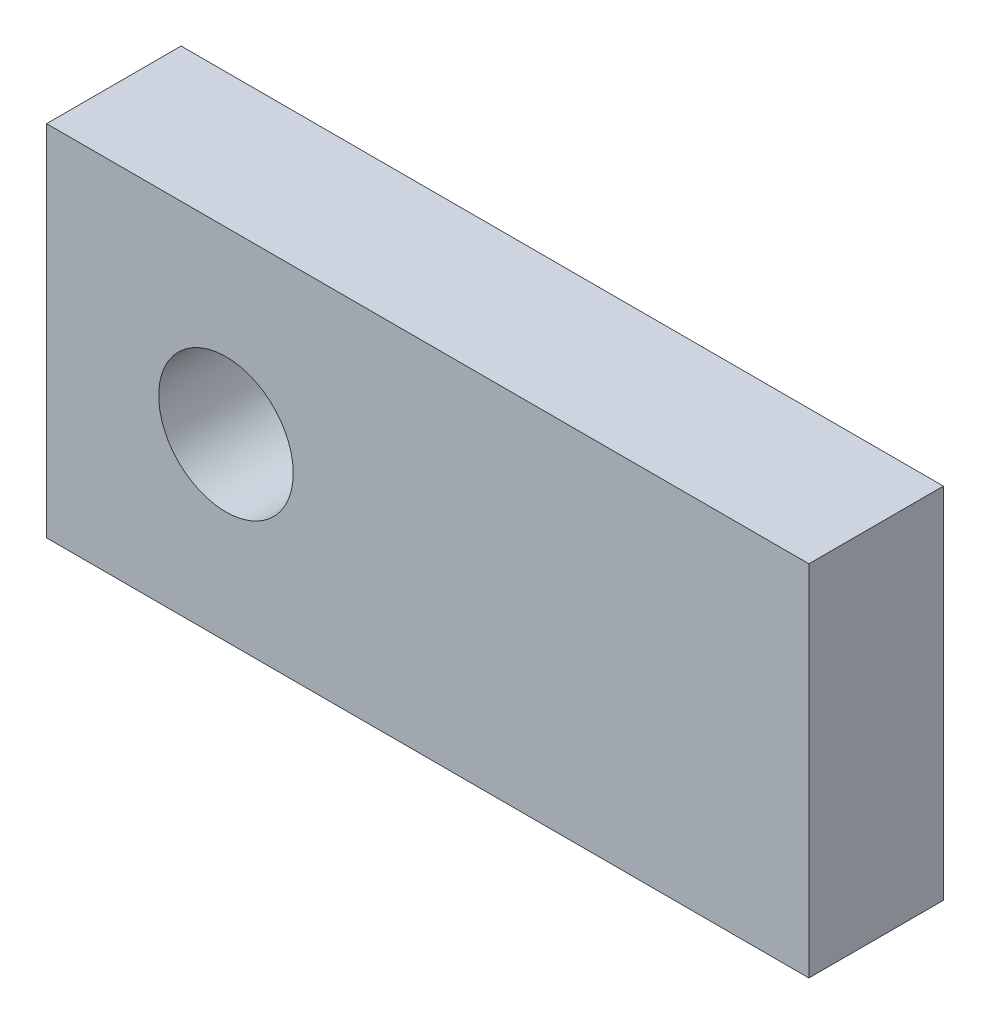
SolidWorks part; units mm, degrees
ref_plane "Спереди" through (0, 0, 0) normal (0, 0, 1) x (1, 0, 0)
ref_plane "Сверху" through (0, 0, 0) normal (0, 1, 0) x (1, 0, 0)
ref_plane "Справа" through (0, 0, 0) normal (1, 0, 0) x (0, 0, -1)
other "Configuration Table"
sketch "Эскиз1" plane through (0, 0, 0) normal (0, 0, 1) x (1, 0, 0)
  line L0 (8.5, 8) -> (8.5, 0) construction
  line L1 (0, 0) -> (17, 0)
  line L2 (0, 0) -> (0, 8)
  line L3 (0, 8) -> (17, 8)
  line L4 (17, 0) -> (17, 8)
  line L5 (0, 4) -> (17, 4) construction
  dimension "D1" = 17
  dimension "D2" = 8
extrude "Бобышка-Вытянуть1" add sketch "Эскиз1" along normal blind 3
sketch "Эскиз2" plane through (0, 0, 3) normal (0, 0, 1) x (1, 0, 0)
  line L0 (0, 0) -> (17, 0) construction
  line L1 (0, 8) -> (0, 0) construction
  circle A0 centre (4, 4) radius 1.5
  dimension "D1" = 3
  dimension "D2" = 4
  dimension "D3" = 4
extrude "Вырез-Вытянуть1" cut sketch "Эскиз2" against normal through all
